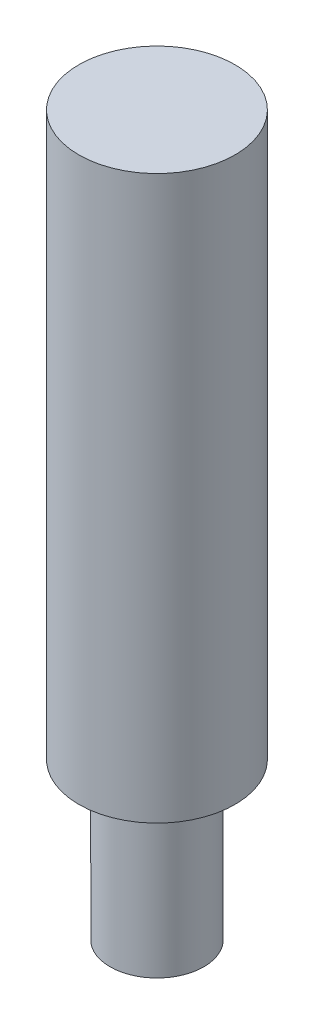
SolidWorks part; units mm, degrees
ref_plane "Front Plane" through (0, 0, 0) normal (0, 0, 1) x (1, 0, 0)
ref_plane "Top Plane" through (0, 0, 0) normal (0, 1, 0) x (1, 0, 0)
ref_plane "Right Plane" through (0, 0, 0) normal (1, 0, 0) x (0, 0, -1)
sketch "Sketch1" plane through (0, 0, 0) normal (0, 1, 0) x (1, 0, 0)
  circle A0 centre (0, 0) radius 2.5
  dimension "D1" = 5
extrude "Boss-Extrude1" add sketch "Sketch1" along normal blind 18
sketch "Sketch2" plane through (0, 0, 0) normal (0, -1, 0) x (-1, 0, 0)
  circle A0 centre (0, 0) radius 1.5
  dimension "D1" = 3
extrude "Boss-Extrude2" add sketch "Sketch2" along normal blind 5
